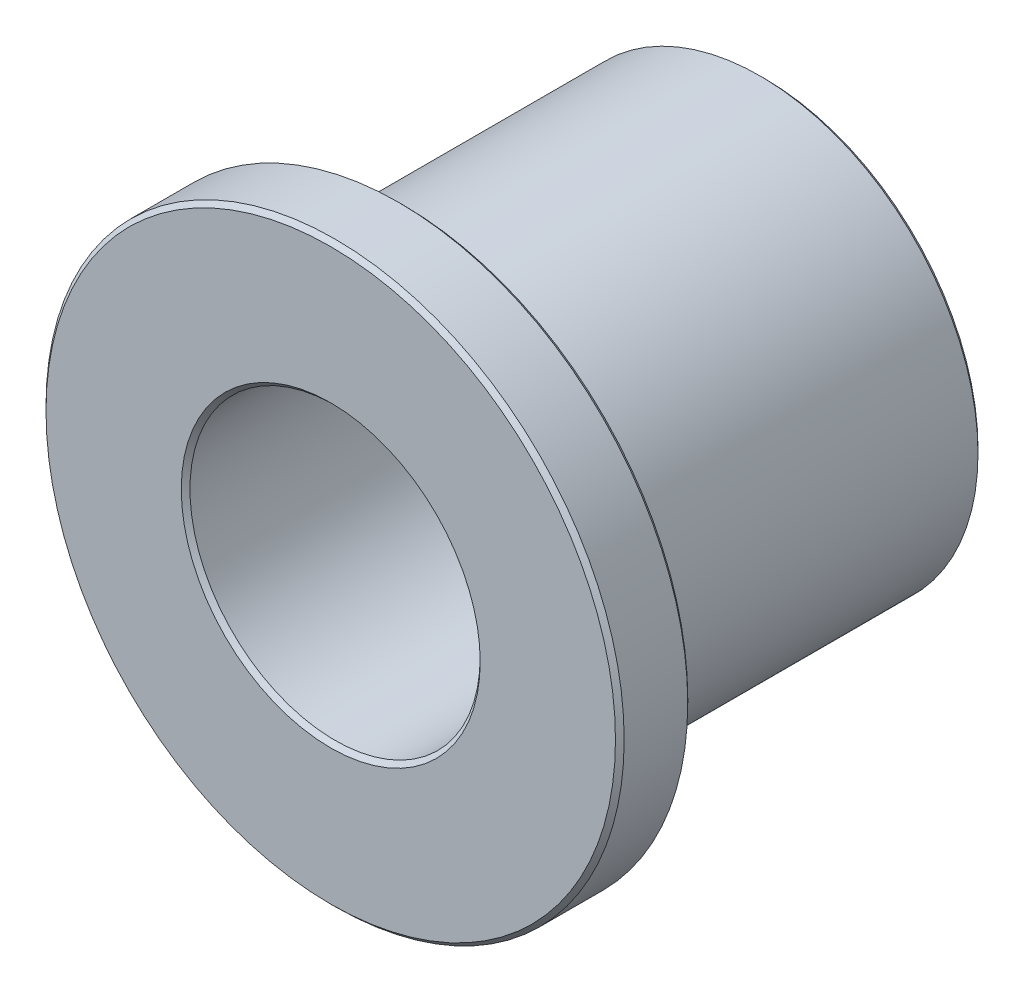
SolidWorks part; units mm, degrees
ref_plane "Front" through (0, 0, 0) normal (0, 0, 1) x (1, 0, 0)
ref_plane "Top" through (0, 0, 0) normal (0, 1, 0) x (1, 0, 0)
ref_plane "Right" through (0, 0, 0) normal (1, 0, 0) x (0, 0, -1)
sketch "Sketch1" plane through (0, 0, 0) normal (0, 0, 1) x (1, 0, 0)
  circle A0 centre (0, 0) radius 3.1877
  circle A1 centre (0, 0) radius 4.7879
  circle A2 centre (0, 0) radius 6.35
  dimension "ID" = 6.3754
  dimension "OD" = 9.5758
  dimension "Flange OD" = 12.7
sketch "Sketch2" plane through (0, 0, 0) normal (1, 0, 0) x (0, 0, -1)
  line L0 (-4.7625, -6.35) -> (4.7625, -6.35) construction
  line L1 (0, 6.35) -> (0, -6.35) construction
  line L3 (-3.175, 4.7879) -> (4.7625, 4.7879) construction
  point P3 (0, -6.35)
  point P7 (0, 4.7879)
  point P9 (-3.175, -6.35)
  point P10 (-4.7625, 6.35)
  point P23 (0, 6.35)
  dimension "Flange Thickness" = 1.5875
  dimension "Length" = 9.525
sketch "Sketch3" plane through (0, 0, 0) normal (0, 0, 1) x (1, 0, 0)
  circle A0 centre (0, 0) radius 6.35 construction
  circle A1 centre (0, 0) radius 6.35
  circle A2 centre (0, 0) radius 3.1877 construction
  circle A3 centre (0, 0) radius 3.1877
extrude "Boss-Extrude1" add sketch "Sketch3" against normal up to vertex (-3.175 mm away) from vertex at 4.7625 starting at point (0, -6.35, 4.7625)
sketch "Sketch4" plane through (0, 0, 0) normal (0, 0, 1) x (1, 0, 0)
  circle A0 centre (0, 0) radius 3.1877 construction
  circle A1 centre (0, 0) radius 4.7879 construction
  circle A2 centre (0, 0) radius 3.1877
  circle A3 centre (0, 0) radius 4.7879
extrude "Boss-Extrude2" add sketch "Sketch4" against normal up to vertex (4.7625 mm away) from vertex at 3.175 starting at point (0, -6.35, 3.175)
chamfer "Chamfer1" distance 0.0956 angle 45 6 edges at (3.1877, 0, 4.7625) (6.35, 0, 4.7625) (6.35, 0, 3.175) (4.7879, 0, 3.175) (3.1877, 0, -4.7625) (4.7879, 0, -4.7625)
equation "\"D1@Chamfer1\"=\"ID@Sketch1\"*0.015"
